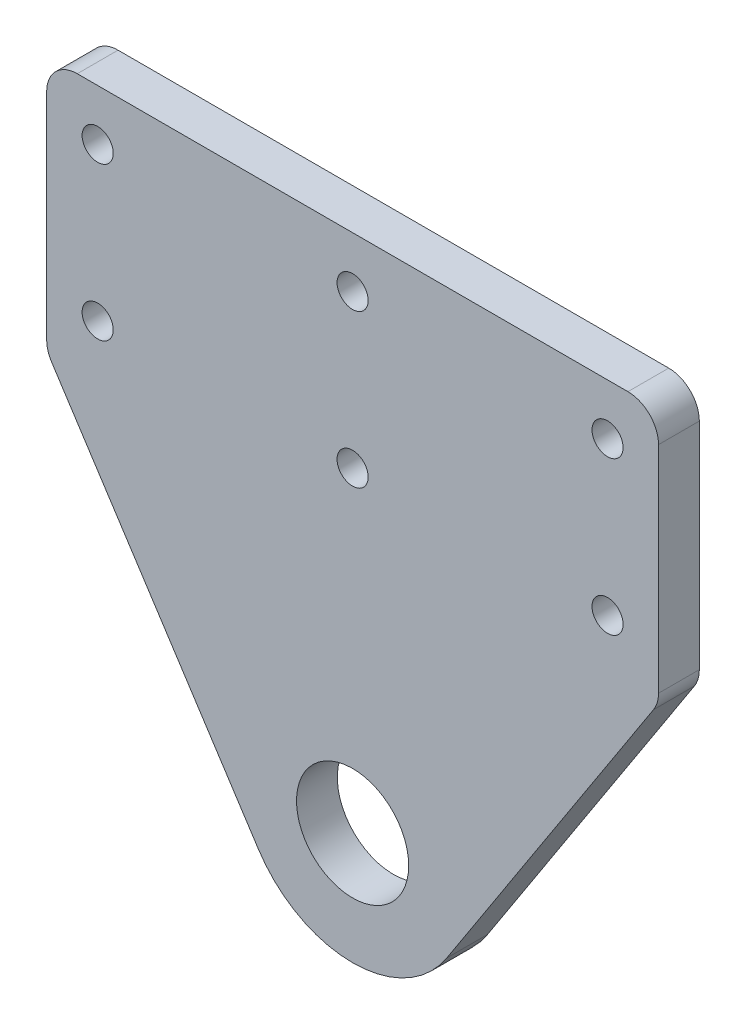
SolidWorks part; units mm, degrees
material "Thornel Mat VMA"
ref_plane "前视基准面" through (0, 0, 0) normal (0, 0, 1) x (1, 0, 0)
ref_plane "上视基准面" through (0, 0, 0) normal (0, 1, 0) x (1, 0, 0)
ref_plane "右视基准面" through (0, 0, 0) normal (1, 0, 0) x (0, 0, -1)
sketch "草图1" plane through (0, 0, 0) normal (0, 0, 1) x (1, 0, 0)
  line L0 (-9.2255, -5.9909) -> (-30, 26)
  line L1 (-30, 26) -> (-30, 51)
  line L2 (-30, 51) -> (30, 51)
  line L3 (0, 51) -> (0, 0) construction
  line L4 (30, 26) -> (30, 51)
  line L5 (9.2255, -5.9909) -> (30, 26)
  circle A0 centre (0, 0) radius 5.5
  arc A1 (-9.2255, -5.9909) -> (9.2255, -5.9909) centre (0, 0) ccw
  dimension "D1" = 11
  dimension "D2" = 22
  dimension "D3" = 60
  dimension "D4" = 51
  dimension "D5" = 25
extrude "凸台-拉伸1" add sketch "草图1" along normal blind 4
sketch "草图2" plane through (0, 0, 4) normal (0, 0, 1) x (1, 0, 0)
  circle A0 centre (0, 0) radius 17.5 construction
  circle A1 centre (0, 17.5) radius 2.025
  circle A2 centre (12.3744, 12.3744) radius 2.025
  circle A3 centre (17.5, 0) radius 2.025
  circle A4 centre (12.3744, -12.3744) radius 2.025
  circle A5 centre (0, -17.5) radius 2.025
  circle A6 centre (-12.3744, -12.3744) radius 2.025
  circle A7 centre (-17.5, 0) radius 2.025
  circle A8 centre (-12.3744, 12.3744) radius 2.025
  point P21 (0, 0)
  dimension "D1" = 35
  dimension "D2" = 4.05
  dimension "D3" = 8
extrude "切除-拉伸1" [suppressed] cut sketch "草图2" against normal blind 43
fillet "圆角1" radius 3 4 edges at (-30, 51, 2) (-30, 26, 2) (30, 26, 2) (30, 51, 2)
sketch "草图3" plane through (0, 0, 0) normal (0, 0, -1) x (-1, 0, 0)
  line L1 (-25, 31) -> (25, 31) construction
  line L2 (-25, 31) -> (-25, 46) construction
  line L3 (-25, 46) -> (25, 46) construction
  line L4 (25, 31) -> (25, 46) construction
  line L5 (0, 46) -> (0, 31) construction
  line L6 (-25, 38.5) -> (25, 38.5) construction
  circle A6 centre (25, 31) radius 1.525
  circle A7 centre (25, 46) radius 1.525
  circle A8 centre (0, 31) radius 1.525
  circle A9 centre (0, 46) radius 1.525
  circle A10 centre (-25, 31) radius 1.525
  circle A11 centre (-25, 46) radius 1.525
  point P1 (0, 38.5)
  point P3 (25, 32.525)
  dimension "D4" = 3.05
  dimension "D1" = 15
  dimension "D2" = 50
  dimension "D3" = 38.5
extrude "切除-拉伸2" cut sketch "草图3" against normal blind 10
